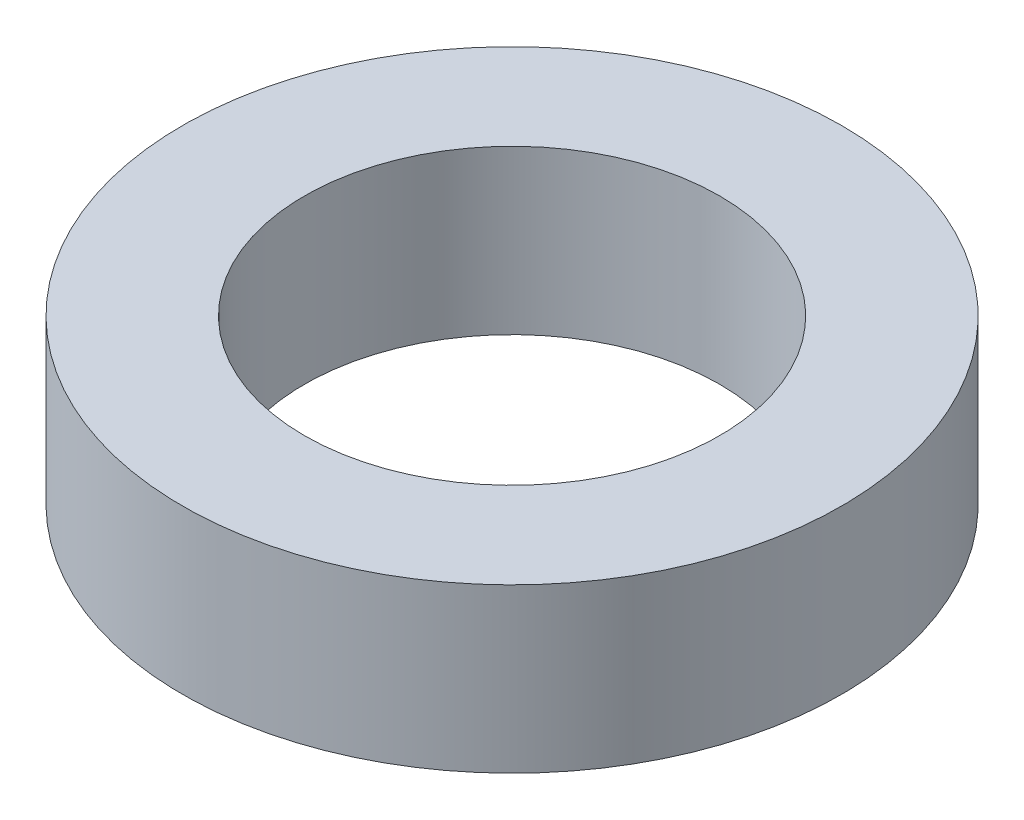
SolidWorks part; units mm, degrees
ref_plane "Front" through (0, 0, 0) normal (0, 0, 1) x (1, 0, 0)
ref_plane "Top" through (0, 0, 0) normal (0, 1, 0) x (1, 0, 0)
ref_plane "Right" through (0, 0, 0) normal (1, 0, 0) x (0, 0, -1)
sketch "Sketch1" plane through (0, 0, 0) normal (0, 1, 0) x (1, 0, 0)
  circle A0 centre (0, 0) radius 3.15
  circle A1 centre (0, 0) radius 5
extrude "Boss-Extrude1" add sketch "Sketch1" along normal blind 2.475
